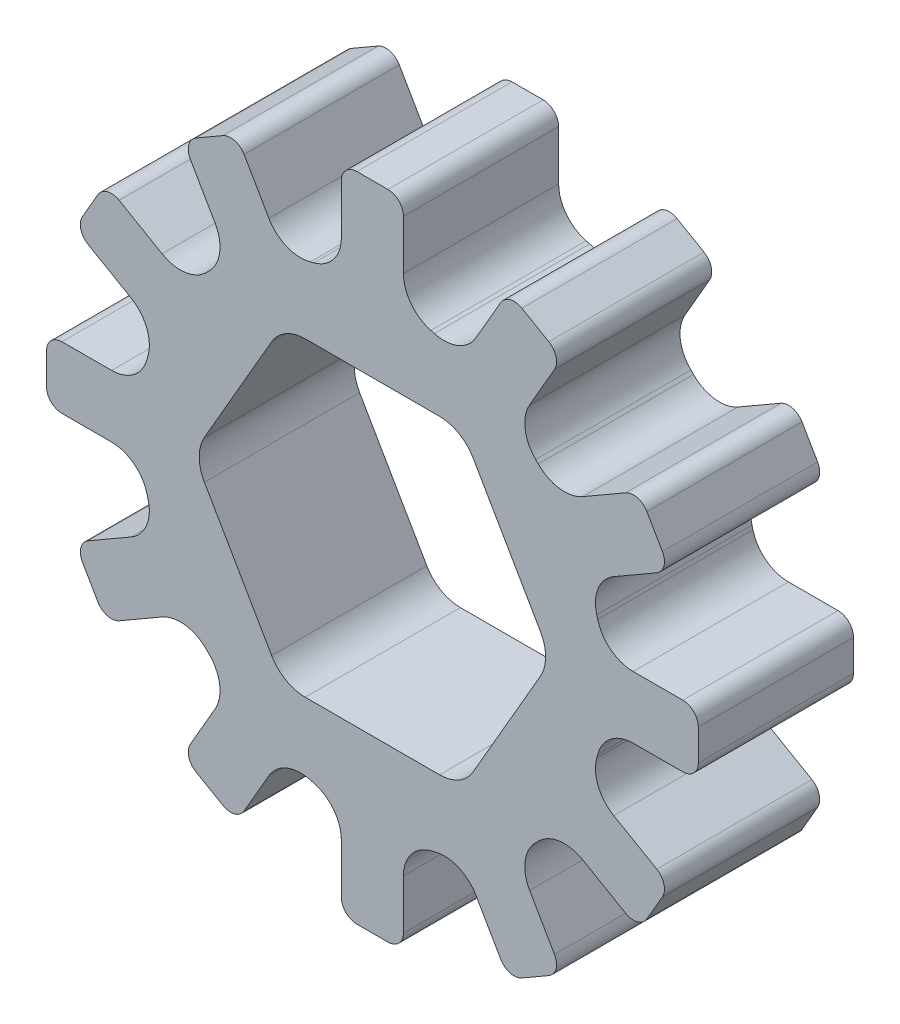
SolidWorks part; units mm, degrees
material "6061 Alloy"
ref_plane "Front Plane" through (0, 0, 0) normal (0, 0, 1) x (1, 0, 0)
ref_plane "Top Plane" through (0, 0, 0) normal (0, 1, 0) x (1, 0, 0)
ref_plane "Right Plane" through (0, 0, 0) normal (1, 0, 0) x (0, 0, -1)
sketch "Sketch1" plane through (0, 0, 0) normal (0, 0, 1) x (1, 0, 0)
  line L0 (0, 0) -> (0, 9.525) construction
  line L7 (-1.27, 10.6703) -> (-1.27, 12.7)
  line L8 (-0.635, 13.335) -> (0.635, 13.335)
  line L9 (1.27, 12.7) -> (1.27, 10.6703)
  line L10 (4.2353, 9.8757) -> (5.2501, 11.6335)
  line L11 (6.1176, 11.8659) -> (7.2174, 11.2309)
  line L12 (7.4499, 10.3635) -> (6.435, 8.6057)
  line L13 (8.6057, 6.435) -> (10.3635, 7.4499)
  line L14 (11.2309, 7.2174) -> (11.8659, 6.1176)
  line L15 (11.6335, 5.2501) -> (9.8757, 4.2353)
  line L16 (10.6703, 1.27) -> (12.7, 1.27)
  line L17 (13.335, 0.635) -> (13.335, -0.635)
  line L18 (12.7, -1.27) -> (10.6703, -1.27)
  line L19 (9.8757, -4.2353) -> (11.6335, -5.2501)
  line L20 (11.8659, -6.1176) -> (11.2309, -7.2174)
  line L21 (10.3635, -7.4499) -> (8.6057, -6.435)
  line L22 (6.435, -8.6057) -> (7.4499, -10.3635)
  line L23 (7.2174, -11.2309) -> (6.1176, -11.8659)
  line L24 (5.2501, -11.6335) -> (4.2353, -9.8757)
  line L25 (1.27, -10.6703) -> (1.27, -12.7)
  line L26 (0.635, -13.335) -> (-0.635, -13.335)
  line L27 (-1.27, -12.7) -> (-1.27, -10.6703)
  line L28 (-4.2353, -9.8757) -> (-5.2501, -11.6335)
  line L29 (-6.1176, -11.8659) -> (-7.2174, -11.2309)
  line L30 (-7.4499, -10.3635) -> (-6.435, -8.6057)
  line L31 (-8.6057, -6.435) -> (-10.3635, -7.4499)
  line L32 (-11.2309, -7.2174) -> (-11.8659, -6.1176)
  line L33 (-11.6335, -5.2501) -> (-9.8757, -4.2353)
  line L34 (-10.6703, -1.27) -> (-12.7, -1.27)
  line L35 (-13.335, -0.635) -> (-13.335, 0.635)
  line L36 (-12.7, 1.27) -> (-10.6703, 1.27)
  line L37 (-9.8757, 4.2353) -> (-11.6335, 5.2501)
  line L38 (-11.8659, 6.1176) -> (-11.2309, 7.2174)
  line L39 (-10.3635, 7.4499) -> (-8.6057, 6.435)
  line L40 (-6.435, 8.6057) -> (-7.4499, 10.3635)
  line L41 (-7.2174, 11.2309) -> (-6.1176, 11.8659)
  line L42 (-5.2501, 11.6335) -> (-4.2353, 9.8757)
  line L43 (0, 0) -> (2.3922, 9.2197) construction
  line L44 (-2.3922, 9.2197) -> (-2.5381, 9.1806)
  line L45 (2.5381, 9.1806) -> (2.3922, 9.2197)
  line L46 (6.7884, 6.6816) -> (6.6816, 6.7884)
  line L47 (9.2197, 2.3922) -> (9.1806, 2.5381)
  line L48 (9.1806, -2.5381) -> (9.2197, -2.3922)
  line L49 (6.6816, -6.7884) -> (6.7884, -6.6816)
  line L50 (2.3922, -9.2197) -> (2.5381, -9.1806)
  line L51 (-2.5381, -9.1806) -> (-2.3922, -9.2197)
  line L52 (-6.7884, -6.6816) -> (-6.6816, -6.7884)
  line L53 (-9.2197, -2.3922) -> (-9.1806, -2.5381)
  line L54 (-9.1806, 2.5381) -> (-9.2197, 2.3922)
  line L55 (-6.6816, 6.7884) -> (-6.7884, 6.6816)
  line L56 (0, 0) -> (-2.5381, 9.1806) construction
  line L57 (55, 0) -> (-55, 0) construction
  line L58 (-3.6662, 6.35) -> (-7.3323, 0)
  line L59 (-7.3323, 0) -> (-3.6662, -6.35)
  line L60 (-3.6662, -6.35) -> (3.6662, -6.35)
  line L61 (3.6662, -6.35) -> (7.3323, 0)
  line L62 (7.3323, 0) -> (3.6662, 6.35)
  line L63 (3.6662, 6.35) -> (-3.6662, 6.35)
  circle A1 centre (0, 0) radius 9.525 construction
  arc A2 (-2.3922, 9.2197) -> (-1.27, 10.6703) centre (-2.7686, 10.6703) ccw
  arc A3 (0.635, 13.335) -> (1.27, 12.7) centre (0.635, 12.7) cw
  arc A4 (1.27, 10.6703) -> (2.3922, 9.2197) centre (2.7686, 10.6703) ccw
  arc A5 (-1.27, 12.7) -> (-0.635, 13.335) centre (-0.635, 12.7) cw
  arc A6 (2.5381, 9.1806) -> (4.2353, 9.8757) centre (2.9375, 10.625) ccw
  arc A7 (7.2174, 11.2309) -> (7.4499, 10.3635) centre (6.8999, 10.681) cw
  arc A8 (6.435, 8.6057) -> (6.6816, 6.7884) centre (7.7328, 7.8564) ccw
  arc A9 (5.2501, 11.6335) -> (6.1176, 11.8659) centre (5.8001, 11.316) cw
  arc A10 (6.7884, 6.6816) -> (8.6057, 6.435) centre (7.8564, 7.7328) ccw
  arc A11 (11.8659, 6.1176) -> (11.6335, 5.2501) centre (11.316, 5.8001) cw
  arc A12 (9.8757, 4.2353) -> (9.1806, 2.5381) centre (10.625, 2.9375) ccw
  arc A13 (10.3635, 7.4499) -> (11.2309, 7.2174) centre (10.681, 6.8999) cw
  arc A14 (9.2197, 2.3922) -> (10.6703, 1.27) centre (10.6703, 2.7686) ccw
  arc A15 (13.335, -0.635) -> (12.7, -1.27) centre (12.7, -0.635) cw
  arc A16 (10.6703, -1.27) -> (9.2197, -2.3922) centre (10.6703, -2.7686) ccw
  arc A17 (12.7, 1.27) -> (13.335, 0.635) centre (12.7, 0.635) cw
  arc A18 (9.1806, -2.5381) -> (9.8757, -4.2353) centre (10.625, -2.9375) ccw
  arc A19 (11.2309, -7.2174) -> (10.3635, -7.4499) centre (10.681, -6.8999) cw
  arc A20 (8.6057, -6.435) -> (6.7884, -6.6816) centre (7.8564, -7.7328) ccw
  arc A21 (11.6335, -5.2501) -> (11.8659, -6.1176) centre (11.316, -5.8001) cw
  arc A22 (6.6816, -6.7884) -> (6.435, -8.6057) centre (7.7328, -7.8564) ccw
  arc A23 (6.1176, -11.8659) -> (5.2501, -11.6335) centre (5.8001, -11.316) cw
  arc A24 (4.2353, -9.8757) -> (2.5381, -9.1806) centre (2.9375, -10.625) ccw
  arc A25 (7.4499, -10.3635) -> (7.2174, -11.2309) centre (6.8999, -10.681) cw
  arc A26 (2.3922, -9.2197) -> (1.27, -10.6703) centre (2.7686, -10.6703) ccw
  arc A27 (-0.635, -13.335) -> (-1.27, -12.7) centre (-0.635, -12.7) cw
  arc A28 (-1.27, -10.6703) -> (-2.3922, -9.2197) centre (-2.7686, -10.6703) ccw
  arc A29 (1.27, -12.7) -> (0.635, -13.335) centre (0.635, -12.7) cw
  arc A30 (-2.5381, -9.1806) -> (-4.2353, -9.8757) centre (-2.9375, -10.625) ccw
  arc A31 (-7.2174, -11.2309) -> (-7.4499, -10.3635) centre (-6.8999, -10.681) cw
  arc A32 (-6.435, -8.6057) -> (-6.6816, -6.7884) centre (-7.7328, -7.8564) ccw
  arc A33 (-5.2501, -11.6335) -> (-6.1176, -11.8659) centre (-5.8001, -11.316) cw
  arc A34 (-6.7884, -6.6816) -> (-8.6057, -6.435) centre (-7.8564, -7.7328) ccw
  arc A35 (-11.8659, -6.1176) -> (-11.6335, -5.2501) centre (-11.316, -5.8001) cw
  arc A36 (-9.8757, -4.2353) -> (-9.1806, -2.5381) centre (-10.625, -2.9375) ccw
  arc A37 (-10.3635, -7.4499) -> (-11.2309, -7.2174) centre (-10.681, -6.8999) cw
  arc A38 (-9.2197, -2.3922) -> (-10.6703, -1.27) centre (-10.6703, -2.7686) ccw
  arc A39 (-13.335, 0.635) -> (-12.7, 1.27) centre (-12.7, 0.635) cw
  arc A40 (-10.6703, 1.27) -> (-9.2197, 2.3922) centre (-10.6703, 2.7686) ccw
  arc A41 (-12.7, -1.27) -> (-13.335, -0.635) centre (-12.7, -0.635) cw
  arc A42 (-9.1806, 2.5381) -> (-9.8757, 4.2353) centre (-10.625, 2.9375) ccw
  arc A43 (-11.2309, 7.2174) -> (-10.3635, 7.4499) centre (-10.681, 6.8999) cw
  arc A44 (-8.6057, 6.435) -> (-6.7884, 6.6816) centre (-7.8564, 7.7328) ccw
  arc A45 (-11.6335, 5.2501) -> (-11.8659, 6.1176) centre (-11.316, 5.8001) cw
  arc A46 (-6.6816, 6.7884) -> (-6.435, 8.6057) centre (-7.7328, 7.8564) ccw
  arc A47 (-6.1176, 11.8659) -> (-5.2501, 11.6335) centre (-5.8001, 11.316) cw
  arc A48 (-4.2353, 9.8757) -> (-2.5381, 9.1806) centre (-2.9375, 10.625) ccw
  arc A49 (-7.4499, 10.3635) -> (-7.2174, 11.2309) centre (-6.8999, 10.681) cw
  circle A50 centre (0, 0) radius 6.35 construction
  point P1 (0, 13.335)
  point P26 (6.6675, 11.5484)
  point P39 (11.5484, 6.6675)
  point P52 (13.335, 0)
  point P65 (11.5484, -6.6675)
  point P78 (6.6675, -11.5484)
  point P91 (0, -13.335)
  point P104 (-6.6675, -11.5484)
  point P117 (-11.5484, -6.6675)
  point P130 (-13.335, 0)
  point P143 (-11.5484, 6.6675)
  point P156 (-6.6675, 11.5484)
  dimension "D2" = 19.05
  dimension "D3" = 1.4986
  dimension "D6" = 0.635
  dimension "D11" = 12.7
  dimension "D4" = 2.54
  dimension "D5" = 3.81
  dimension "D8" = 9.525
  dimension "D9" = 12
  dimension "D10" = 9.525
  dimension "D7" = 12
extrude "Boss-Extrude1" add sketch "Sketch1" along normal mid plane 6.35 contours A49 L40 A46 L55 A44 L39 A43 L38 A45 L37 A42 L54 A40 L36 A39 L35 A41 L34 A38 L53 A36 L33 A35 L32 A37 L31 A34 L52 A32 L30 A31 L29 A33 L28 A30 L51 A28 L27 A27 L26 A29 L25 A26 L50 A24 L24 A23 L23 A25 L22 A22
fillet "Fillet1" radius 1.5875 6 edges at (3.6662, 6.35, 0) (7.3323, 0, 0) (3.6662, -6.35, 0) (-3.6662, -6.35, 0) (-7.3323, 0, 0) (-3.6662, 6.35, 0)
